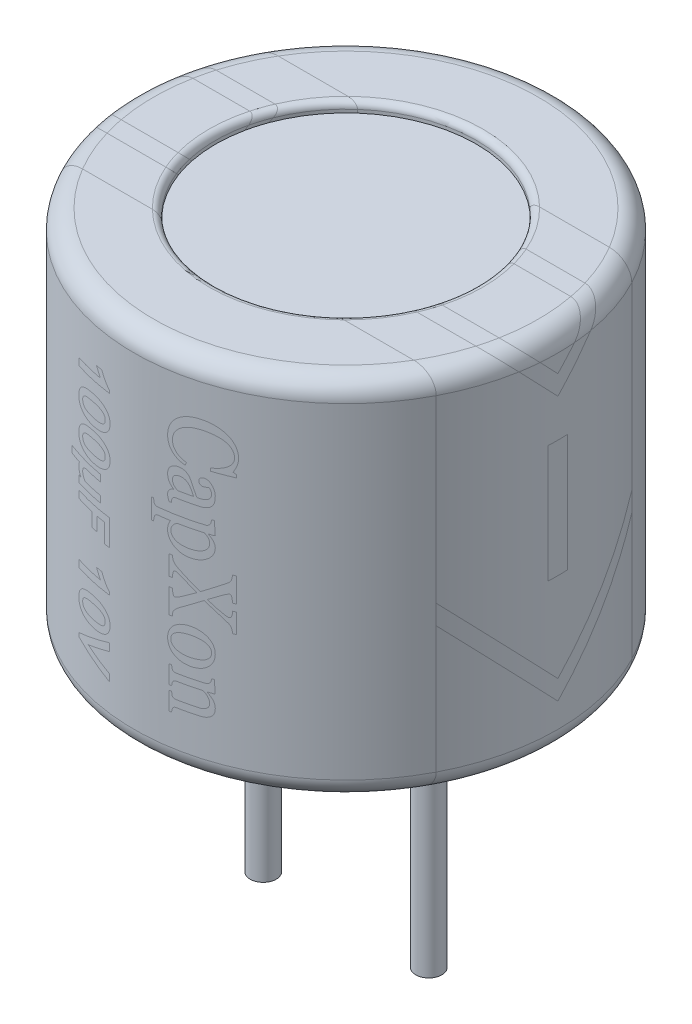
SolidWorks part; units mm, degrees
ref_plane "Спереди" through (0, 0, 0) normal (0, 0, 1) x (1, 0, 0)
ref_plane "Сверху" through (0, 0, 0) normal (0, 1, 0) x (1, 0, 0)
ref_plane "Справа" through (0, 0, 0) normal (1, 0, 0) x (0, 0, -1)
sketch "Эскиз1" plane through (0, 0, 0) normal (0, 1, 0) x (1, 0, 0)
  circle A0 centre (0, 0) radius 3.25
  dimension "D1" = 6.5
extrude "Бобышка-Вытянуть1" add sketch "Эскиз1" along normal blind 5.6
sketch "Эскиз2" plane through (0, 5.6, 0) normal (0, 1, 0) x (1, 0, 0)
  circle A0 centre (0, 0) radius 2
  dimension "D1" = 4
extrude "Вырез-Вытянуть1" cut sketch "Эскиз2" against normal blind 0.15
sketch "Эскиз3" plane through (0, 0, 0) normal (0, -1, 0) x (1, 0, 0)
  circle A0 centre (0, 0) radius 2
  dimension "D1" = 4
extrude "Вырез-Вытянуть2" cut sketch "Эскиз3" against normal blind 0.15
sketch "Эскиз4" plane through (0, 0.15, 0) normal (0, -1, 0) x (1, 0, 0)
  line L0 (0, 1.6012) -> (0, -1.256) construction
  circle A0 centre (-1.27, 0) radius 0.2
  circle A1 centre (1.27, 0) radius 0.2
  dimension "D1" = 0.4
  dimension "D2" = 1.27
extrude "Бобышка-Вытянуть2" add sketch "Эскиз4" along normal blind 4 separate body
fillet "Скругление1" radius 0.3 2 edges at (0, 0, 3.25) (0, 5.6, 3.25)
fillet "Скругление2" radius 0.1 2 edges at (0, 0, -2) (0, 5.6, 2)
ref_plane "Плоскость1" through (-3.25, 0, 0) normal (-1, 0, 0) x (0, -1, 0)
sketch "Эскиз5" plane through (-3.25, 0, 0) normal (-1, 0, 0) x (0, -1, 0)
  line L0 (-5.6, 2.95) -> (-5.6, -2.95) construction
  line L1 (-7.2927, 1.5) -> (-6.5927, 1.5)
  line L2 (-7.2927, 1.5) -> (-7.2927, -1.5)
  line L3 (-7.2927, -1.5) -> (-6.5927, -1.5)
  line L4 (1.7073, 1.5) -> (1.7073, -1.5)
  line L5 (-7.2927, 1.5) -> (1.7073, -1.5) construction
  line L6 (-7.2927, -1.5) -> (1.7073, 1.5) construction
  line L7 (-7.7807, 0) -> (4.2241, 0) construction
  line L8 (-6.2927, 1.5) -> (-4.7256, 0)
  line L9 (-6.2927, -1.5) -> (-4.7256, 0)
  line L10 (-6.5927, 1.5) -> (-5.0256, 0)
  line L11 (-5.0256, 0) -> (-6.5927, -1.5)
  line L12 (-6.2927, -1.5) -> (1.7073, -1.5)
  line L13 (-6.2927, 1.5) -> (1.7073, 1.5)
  line L14 (-2.243, 1.5) -> (-0.6759, 0)
  line L15 (-4.1427, 0.15) -> (-2.3427, 0.15)
  line L16 (-4.1427, 0.15) -> (-4.1427, -0.15)
  line L17 (-4.1427, -0.15) -> (-2.3427, -0.15)
  line L18 (-2.3427, 0.15) -> (-2.3427, -0.15)
  line L19 (-2.243, -1.5) -> (-0.6759, 0)
  line L20 (-2.543, 1.5) -> (-0.9759, 0)
  line L21 (-0.9759, 0) -> (-2.543, -1.5)
  line L22 (-0.0959, 0.15) -> (1.7041, 0.15)
  line L23 (-0.0959, 0.15) -> (-0.0959, -0.15)
  line L24 (-0.0959, -0.15) -> (1.7041, -0.15)
  line L25 (1.7041, 0.15) -> (1.7041, -0.15)
  point P0 (-2.7927, 0)
  point P20 (-4.1427, 0)
  point P27 (0, 0)
  point P28 (0, 0)
  point P33 (-0.0959, 0)
  point P34 (0, 0)
  dimension "D1" = 3
  dimension "D2" = 9
  dimension "D3" = 1.6927
  dimension "D4" = 1
  dimension "D5" = 0.3
  dimension "D6" = 0.3
  dimension "D7" = 0.3
  dimension "D8" = 0.3
  dimension "D9" = 2.2671
  dimension "D10" = 1.8
  dimension "D11" = 0.88
split line "Разделяющая линия1"
ref_plane "Плоскость2" through (0, 0, 3.7) normal (0, 0, 1) x (1, 0, 0)
sketch "Эскиз6" plane through (0, 0, 3.7) normal (0, 0, 1) x (1, 0, 0)
  line L0 (0.5, 5.3) -> (0.5, 0.3) construction
  line L1 (2.8831, 5.3) -> (-2.8831, 5.3) construction
  line L2 (-2.8831, 0.3) -> (2.8831, 0.3) construction
  line L3 (-1, 5.3) -> (-1, 0.3) construction
  text T0 "CapXon" font "Georgia" height 0.8
  text T1 "100µF 10V" font "Trebuchet MS" height 0.6
  dimension "D1" = 0.5
  dimension "D2" = 1
split line "Разделяющая линия2"
